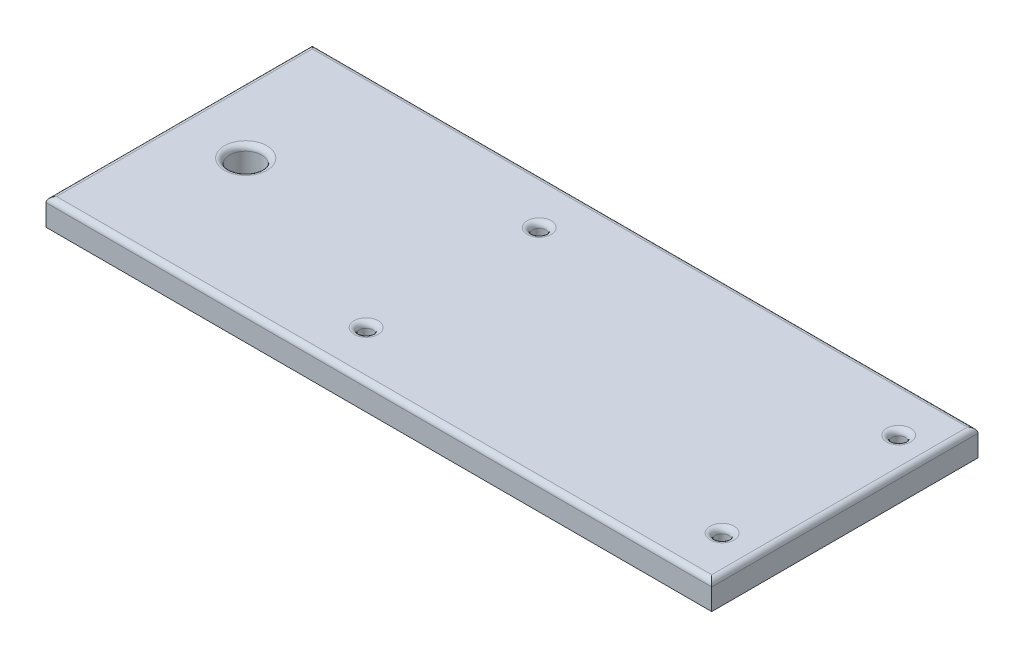
SolidWorks part; units mm, degrees
ref_plane "Front Plane" through (0, 0, 0) normal (0, 0, 1) x (1, 0, 0)
ref_plane "Top Plane" through (0, 0, 0) normal (0, 1, 0) x (1, 0, 0)
ref_plane "Right Plane" through (0, 0, 0) normal (1, 0, 0) x (0, 0, -1)
sketch "Sketch1" plane through (0, 0, 0) normal (0, 1, 0) x (1, 0, 0)
  line L1 (-3175, 1270) -> (3175, 1270)
  line L2 (-3175, 1270) -> (-3175, -1270)
  line L3 (-3175, -1270) -> (3175, -1270)
  line L4 (3175, 1270) -> (3175, -1270)
  line L5 (-3175, 1270) -> (3175, -1270) construction
  line L6 (-3175, -1270) -> (3175, 1270) construction
  circle A0 centre (-2540, 0) radius 152.4
  circle A1 centre (-565.912, 825.5) radius 63.5
  circle A2 centre (-565.912, -825.5) radius 63.5
  circle A3 centre (2829.7005, -825.5) radius 63.5
  circle A4 centre (2863.088, 825.5) radius 63.5
  point P0 (0, 0)
  dimension "D3" = 304.8
  dimension "D10" = 127
  dimension "D1" = 6350
  dimension "D2" = 2540
  dimension "D4" = 2540
  dimension "D5" = 1270
  dimension "D6" = 2863.088
  dimension "D7" = 3429
  dimension "D8" = 1651
  dimension "D9" = 444.5
extrude "Boss-Extrude1" add sketch "Sketch1" along normal blind 254
fillet "Fillet1" radius 50.8 10 edges at (-565.912, 0, 889) (-565.912, 254, 889) (2863.088, 254, -762) (2829.7005, 254, 889) (-565.912, 254, -762) (3175, 254, 0) (-2540, 254, 152.4) (-3175, 254, 0) (0, 254, -1270) (0, 254, 1270)
